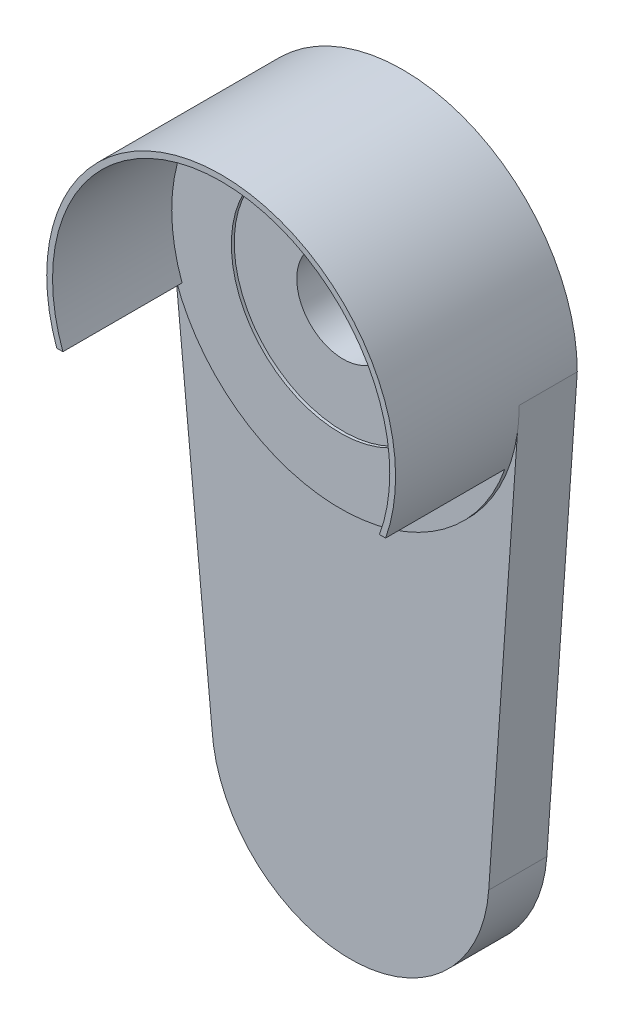
SolidWorks part; units mm, degrees
ref_plane "Front Plane" through (0, 0, 0) normal (0, 0, 1) x (1, 0, 0)
ref_plane "Top Plane" through (0, 0, 0) normal (0, 1, 0) x (1, 0, 0)
ref_plane "Right Plane" through (0, 0, 0) normal (1, 0, 0) x (0, 0, -1)
sketch "Sketch2" plane through (0, 0, 0) normal (0, 0, 1) x (1, 0, 0)
  circle A0 centre (0, 0) radius 120
extrude "Boss-Extrude2" add sketch "Sketch2" along normal blind 85
sketch "Sketch3" plane through (0, 0, 85) normal (0, 0, 1) x (1, 0, 0)
  line L0 (-113.1371, -40) -> (-108.8853, -40)
  line L1 (108.8853, -40) -> (113.1371, -40)
  arc A0 (108.8853, -40) -> (-108.8853, -40) centre (0, 0) ccw
  arc A1 (113.1371, -40) -> (-113.1371, -40) centre (0, 0) ccw
  circle M1 centre (0, 0) radius 120
  dimension "D1" = 40
extrude "Cut-Extrude1" cut sketch "Sketch3" against normal blind 82 contours L1 A0 L0 M1
sketch "Sketch8" plane through (0, 0, 3) normal (0, 0, 1) x (1, 0, 0)
  circle A0 centre (0, 0) radius 75
extrude "Cut-Extrude5" cut sketch "Sketch8" along normal blind 2 and the other way blind 2
sketch "Sketch9" plane through (0, 0, 1) normal (0, 0, 1) x (1, 0, 0)
  line L0 (0, 0) -> (-75, 0) construction
  line L1 (0, 0) -> (0, 75) construction
  circle A0 centre (0, 0) radius 75 construction
  circle A1 centre (0, 0) radius 32
extrude "Cut-Extrude6" cut sketch "Sketch9" against normal blind 5 contours A1
sketch "Sketch12" plane through (0, 0, 0) normal (0, 0, -1) x (-1, 0, 0)
  line L0 (-120, 0) -> (-99.0634, -299.2685)
  line L1 (120, 0) -> (91.3099, -298.625)
  circle A1 centre (0, 0) radius 120 construction
  arc A2 (-99.0634, -299.2685) -> (91.3099, -298.625) centre (-3.8981, -292.6108) ccw
  circle A3 centre (0, 0) radius 120
  circle M3 centre (0, 0) radius 32
  circle M4 centre (0, 0) radius 120
extrude "Boss-Extrude4" add sketch "Sketch12" along normal blind 40 contours L1 L0 M4 M3 | L0 A2 L1 M4
